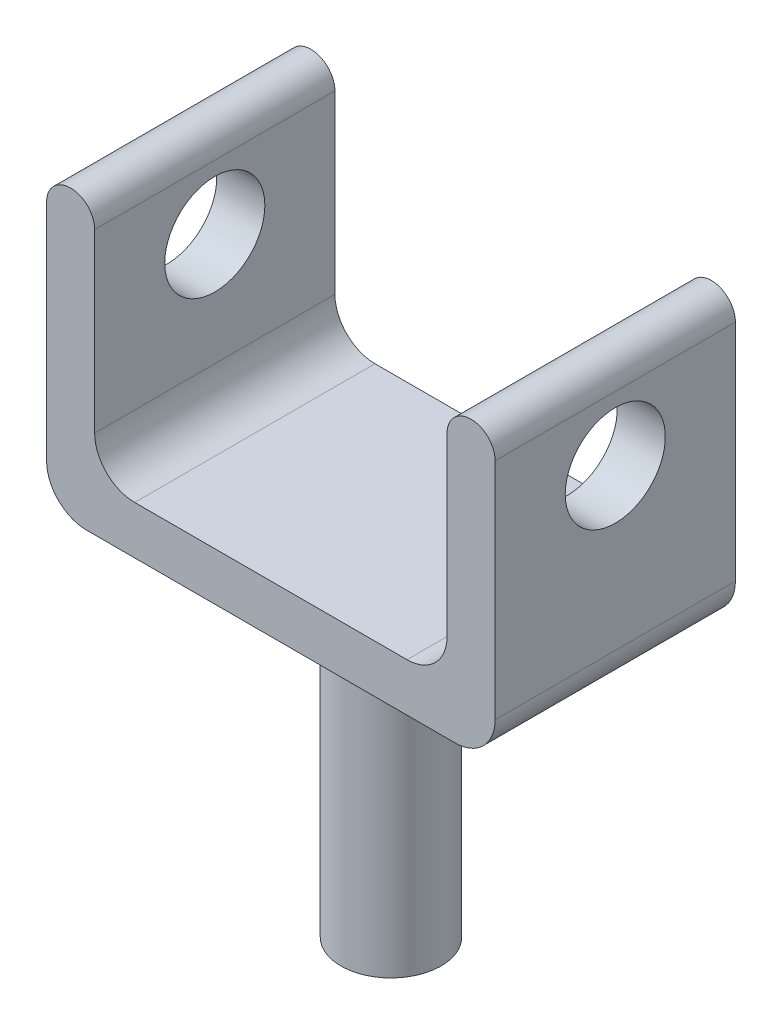
SolidWorks part; units mm, degrees
ref_plane "Front Plane" through (0, 0, 0) normal (0, 0, 1) x (1, 0, 0)
ref_plane "Top Plane" through (0, 0, 0) normal (0, 1, 0) x (1, 0, 0)
ref_plane "Right Plane" through (0, 0, 0) normal (1, 0, 0) x (0, 0, -1)
sketch "Sketch2" plane through (0, 0, 0) normal (0, 0, 1) x (1, 0, 0)
  line L0 (-28.8312, 30) -> (-28.8312, 0)
  line L1 (-28.8312, 0) -> (21.1688, 0)
  line L2 (21.1688, 0) -> (21.1688, 30)
  line L3 (-31.8312, 30) -> (-31.8312, -3)
  line L4 (-31.8312, -3) -> (24.1688, -3)
  line L5 (24.1688, -3) -> (24.1688, 30)
  line L6 (-25.8312, 30) -> (-25.8312, 3)
  line L7 (-25.8312, 3) -> (18.1688, 3)
  line L8 (18.1688, 3) -> (18.1688, 30)
  arc A0 (-31.8312, 30) -> (-25.8312, 30) centre (-28.8312, 30) cw
  arc A1 (24.1688, 30) -> (18.1688, 30) centre (21.1688, 30) ccw
  dimension "D1" = 30
  dimension "D2" = 30
  dimension "D3" = 50
  dimension "D4" = 3
  dimension "D5" = 3
extrude "Boss-Extrude1" add sketch "Sketch2" along normal blind 30
sketch "Sketch3" plane through (0, -3, 0) normal (0, -1, 0) x (1, 0, 0)
  line L0 (-31.8312, 15) -> (24.1688, 15) construction
  line L1 (-31.8312, 30) -> (-31.8312, 0) construction
  line L2 (24.1688, 30) -> (24.1688, 0) construction
  line L3 (-3.8312, 30) -> (-3.8312, 0) construction
  line L4 (-31.8312, 30) -> (24.1688, 30) construction
  line L5 (-31.8312, 0) -> (24.1688, 0) construction
  circle A0 centre (-3.8312, 15) radius 6.25
  dimension "D1" = 12.5
extrude "Boss-Extrude2" add sketch "Sketch3" along normal blind 40
fillet "Fillet1" radius 5 1 edges at (-31.8312, -3, 15)
fillet "Fillet2" radius 5 3 edges at (-25.8312, 3, 15) (18.1688, 3, 15) (24.1688, -3, 15)
sketch "Sketch4" plane through (-31.8312, 0, 0) normal (-1, 0, 0) x (0, 0, 1)
  line L0 (15, 2) -> (15, 22) construction
  line L1 (0, 2) -> (30, 2) construction
  circle A0 centre (15, 22) radius 6.25
  dimension "D2" = 12.5
  dimension "D1" = 20
extrude "Cut-Extrude2" cut sketch "Sketch4" against normal blind 60
